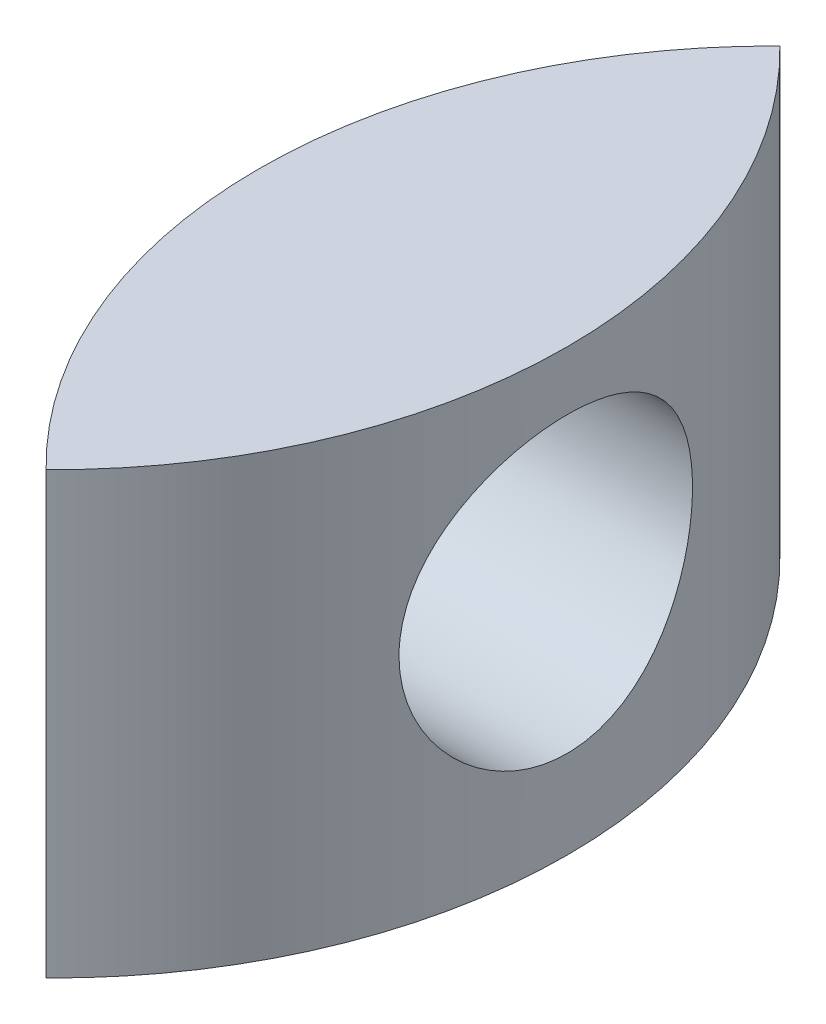
SolidWorks part; units mm, degrees
ref_plane "Front Plane" through (0, 0, 0) normal (0, 0, 1) x (1, 0, 0)
ref_plane "Top Plane" through (0, 0, 0) normal (0, 1, 0) x (1, 0, 0)
ref_plane "Right Plane" through (0, 0, 0) normal (1, 0, 0) x (0, 0, -1)
sketch "Sketch1" plane through (0, 0, 0) normal (0, 1, 0) x (1, 0, 0)
  line L0 (0, 63.5) -> (0, -63.5)
  arc A0 (0, 63.5) -> (0, -63.5) centre (-62.217, 0) cw
  dimension "D1" = 88.9
  dimension "D2" = 127
extrude "Boss-Extrude1" add sketch "Sketch1" along normal blind 76.2
sketch "Sketch2" plane through (0, 0, 0) normal (-1, 0, 0) x (0, 0, 1)
  line L0 (0, 0) -> (0, 40.64) construction
  circle A0 centre (0, 40.64) radius 25.4
  dimension "D1" = 50.8
  dimension "D2" = 40.64
extrude "Cut-Extrude1" cut sketch "Sketch2" against normal up to next
mirror "Mirror1" about plane through (0, 76.2, -63.5) normal (1, 0, 0) of bodies 102
